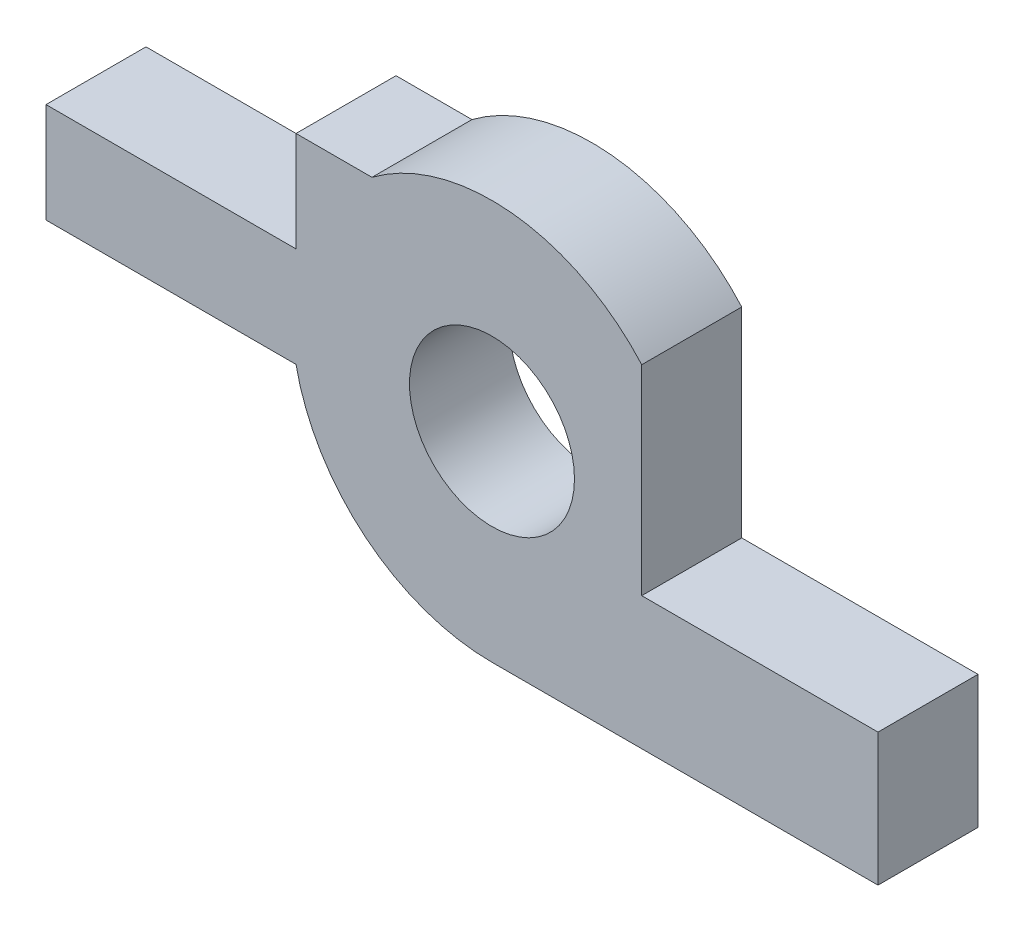
SolidWorks part; units mm, degrees
ref_plane "Front Plane" through (0, 0, 0) normal (0, 0, 1) x (1, 0, 0)
ref_plane "Top Plane" through (0, 0, 0) normal (0, 1, 0) x (1, 0, 0)
ref_plane "Right Plane" through (0, 0, 0) normal (1, 0, 0) x (0, 0, -1)
sketch "Sketch1" plane through (0, 0, 0) normal (0, 0, 1) x (1, 0, 0)
  line L0 (7.72, -4) -> (0, -4)
  line L1 (-3.9192, 1.2) -> (-3.9192, 3.2)
  line L2 (7.72, -1.3485) -> (7.72, -4)
  line L3 (-3.9192, -0.8) -> (-8.9192, -0.8)
  line L4 (2.9949, 2.6515) -> (2.9949, -1.3485)
  line L5 (-8.9192, 1.2) -> (-8.9192, -0.8)
  line L6 (2.9949, -1.3485) -> (7.72, -1.3485)
  line L7 (-3.9192, 1.2) -> (-8.9192, 1.2)
  line L11 (-3.9192, 3.2) -> (-2.4, 3.2)
  circle A0 centre (0, 0) radius 1.65
  arc A1 (2.9949, 2.6515) -> (-2.4, 3.2) centre (0, 0) ccw
  arc A3 (-3.9192, -0.8) -> (0, -4) centre (0, 0) ccw
  dimension "D1" = 3.3
  dimension "D2" = 4
  dimension "D4" = 7.72
  dimension "D3" = 2.9949
  dimension "D5" = 2.4
  dimension "D6" = 3.9192
  dimension "D7" = 8.9192
  dimension "D8" = 1.3485
extrude "Boss-Extrude1" add sketch "Sketch1" along normal blind 2
equation "\"D1@Sketch1\"= 3 + \"tol1@parametersSketch@prostheticParameters.SLDPRT\""
